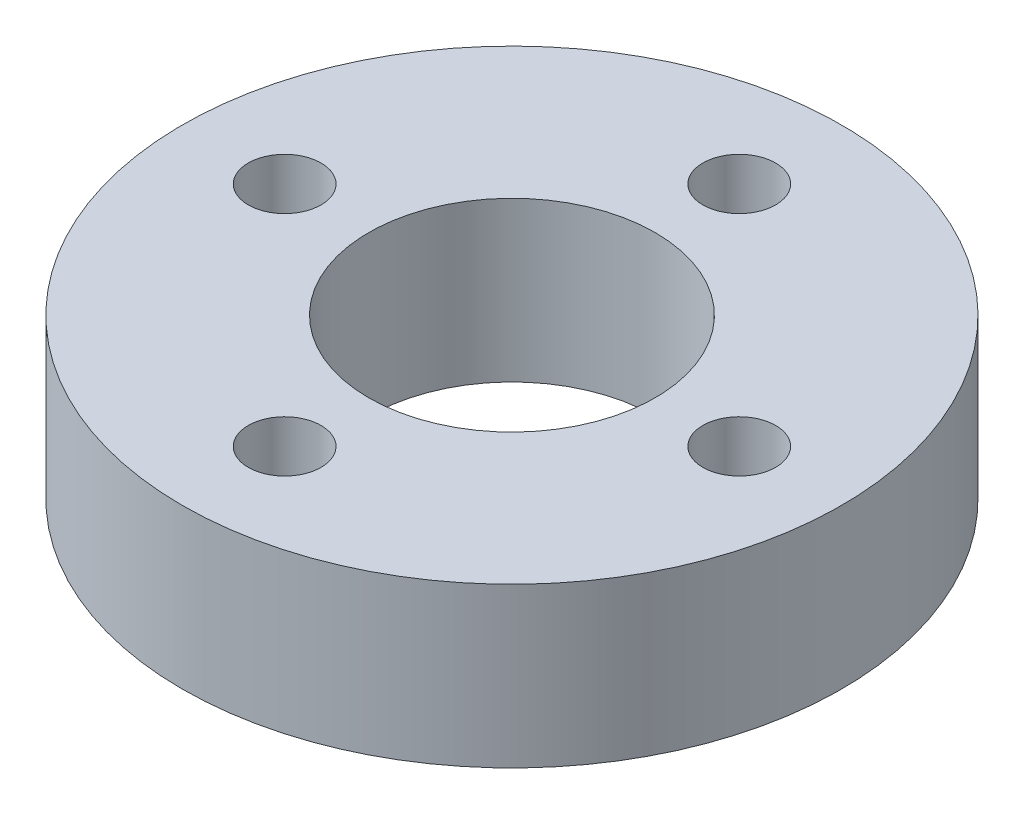
SolidWorks part; units mm, degrees
ref_plane "前视基准面" through (0, 0, 0) normal (0, 0, 1) x (1, 0, 0)
ref_plane "上视基准面" through (0, 0, 0) normal (0, 1, 0) x (1, 0, 0)
ref_plane "右视基准面" through (0, 0, 0) normal (1, 0, 0) x (0, 0, -1)
sketch "草图1" plane through (0, 0, 0) normal (0, 1, 0) x (1, 0, 0)
  circle A0 centre (0, 0) radius 6.3
  circle A1 centre (0, 0) radius 14.5
  circle A2 centre (-10, 0) radius 1.6
  circle A3 centre (0, 10) radius 1.6
  circle A4 centre (10, 0) radius 1.6
  circle A5 centre (0, -10) radius 1.6
  point P15 (0, 0)
  dimension "D1" = 12.6
  dimension "D2" = 29
  dimension "D3" = 3.2
  dimension "D4" = 10
  dimension "D5" = 4
extrude "凸台-拉伸1" add sketch "草图1" along normal blind 7
